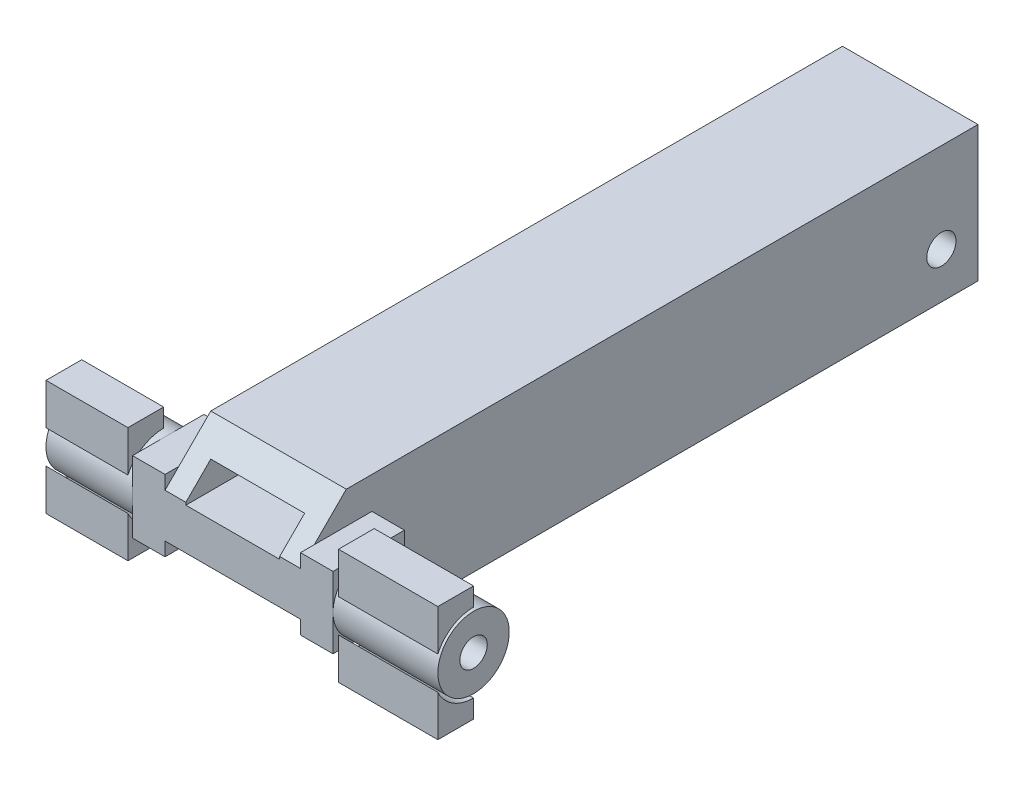
SolidWorks part; units mm, degrees
ref_plane "Спереди" through (0, 0, 0) normal (0, 0, 1) x (1, 0, 0)
ref_plane "Сверху" through (0, 0, 0) normal (0, 1, 0) x (1, 0, 0)
ref_plane "Справа" through (0, 0, 0) normal (1, 0, 0) x (0, 0, -1)
sketch "Эскиз1" plane through (0, 0, 0) normal (1, 0, 0) x (0, 0, -1)
  line L1 (37, -7.4) -> (-37, -7.4)
  line L2 (37, -7.4) -> (37, 7.4)
  line L3 (37, 7.4) -> (-37, 7.4)
  line L4 (-37, -7.4) -> (-37, 7.4)
  line L5 (37, -7.4) -> (-37, 7.4) construction
  line L6 (37, 7.4) -> (-37, -7.4) construction
  point P0 (0, 0)
  dimension "D1" = 14.8
  dimension "D2" = 74
extrude "Бобышка-Вытянуть1" add sketch "Эскиз1" along normal blind 14.8
sketch "Эскиз2" plane through (0, 0, -37) normal (0, 0, -1) x (-1, 0, 0)
  line L0 (0, 7.4) -> (-14.8, -7.4) construction
  line L2 (-2.275, -5.125) -> (-12.525, -5.125)
  line L3 (-2.275, -5.125) -> (-2.275, 5.125)
  line L4 (-2.275, 5.125) -> (-12.525, 5.125)
  line L5 (-12.525, -5.125) -> (-12.525, 5.125)
  line L6 (-2.275, -5.125) -> (-12.525, 5.125) construction
  line L7 (-2.275, 5.125) -> (-12.525, -5.125) construction
  point P4 (-7.4, 0)
  dimension "D1" = 10.25
extrude "Вырез-Вытянуть1" cut sketch "Эскиз2" against normal blind 65
sketch "Эскиз3" plane through (14.8, 0, 0) normal (1, 0, 0) x (0, 0, -1)
  line L0 (37, 0) -> (-37, 0) construction
  line L1 (37, -7.4) -> (37, 7.4) construction
  line L2 (-37, 7.4) -> (-37, -7.4) construction
  circle A0 centre (-33.1, 0) radius 3.9
  dimension "D1" = 7.8
extrude "Бобышка-Вытянуть2" add sketch "Эскиз3" along normal blind 15
sketch "Эскиз4" plane through (0, 0, 0) normal (-1, 0, 0) x (0, 0, 1)
  line L0 (37, 0) -> (-37, 0) construction
  line L1 (37, 7.4) -> (37, -7.4) construction
  line L2 (-37, -7.4) -> (-37, 7.4) construction
  circle A0 centre (33.1, 0) radius 3.9
  dimension "D1" = 7.8
extrude "Бобышка-Вытянуть3" add sketch "Эскиз4" along normal blind 13
chamfer "Фаска1" distance 5 angle 45 2 edges at (7.4, -7.4, 37) (7.4, 7.4, 37)
sketch "Эскиз8" plane through (29.8, 0, 0) normal (1, 0, 0) x (0, 0, -1)
  circle A0 centre (-33.1, 0) radius 1.45
  dimension "D1" = 2.9
extrude "Вырез-Вытянуть4" cut sketch "Эскиз8" against normal through all
sketch "Эскиз9" plane through (0, 0, 0) normal (-1, 0, 0) x (0, 0, 1)
  line L1 (37, -3.9) -> (29.2, -3.9)
  line L2 (37, -3.9) -> (37, 3.9)
  line L3 (37, 3.9) -> (29.2, 3.9)
  line L4 (29.2, -3.9) -> (29.2, 3.9)
  line L5 (37, -3.9) -> (29.2, 3.9) construction
  line L6 (37, 3.9) -> (29.2, -3.9) construction
  circle A0 centre (33.1, 0) radius 3.9 construction
  circle A1 centre (33.1, 0) radius 1.5
  point P0 (33.1, 0)
  point P6 (29.2, 0)
  point P11 (33.1, 3.9)
  dimension "D1" = 3
extrude "Бобышка-Вытянуть4" add sketch "Эскиз9" along normal blind 3.55
sketch "Эскиз10" plane through (14.8, 0, 0) normal (1, 0, 0) x (0, 0, -1)
  line L1 (-37, -3.9) -> (-29.2, -3.9)
  line L2 (-37, -3.9) -> (-37, 3.9)
  line L3 (-37, 3.9) -> (-29.2, 3.9)
  line L4 (-29.2, -3.9) -> (-29.2, 3.9)
  line L5 (-37, -3.9) -> (-29.2, 3.9) construction
  line L6 (-37, 3.9) -> (-29.2, -3.9) construction
  circle A0 centre (-33.1, 0) radius 3.9 construction
  point P0 (-33.1, 0)
  point P6 (-29.2, 0)
  point P9 (-33.1, 3.9)
extrude "Бобышка-Вытянуть5" add sketch "Эскиз10" along normal blind 3.55
sketch "Sketch1" plane through (0, 0, 0) normal (-1, 0, 0) x (0, 0, 1)
  line L0 (-33, 7.4) -> (-33, -7.4) construction
  line L7 (-37, 7.4) -> (32, 7.4) construction
  line L8 (32, -7.4) -> (-37, -7.4) construction
  line L9 (-37, -7.4) -> (-37, 7.4) construction
  circle A0 centre (-33, -2.4) radius 1.6
  dimension "D1" = 3.2
  dimension "D2" = 4
  dimension "D3" = 5
extrude "Cut-Extrude1" cut sketch "Sketch1" against normal through all
sketch "Sketch2" plane through (29.8, 0, 0) normal (1, 0, 0) x (0, 0, -1)
  circle A0 centre (-33.1, 0) radius 1.5
extrude "Cut-Extrude2" cut sketch "Sketch2" against normal through all
sketch "Sketch3" plane through (0, 0, 28) normal (0, 0, -1) x (-1, 0, 0)
  line L0 (-7.4, 5.125) -> (-7.4, -5.125) construction
  line L1 (-2.275, 5.125) -> (-12.525, 5.125) construction
  line L2 (-12.525, -5.125) -> (-2.275, -5.125) construction
  line L4 (-2.275, 2.125) -> (-12.525, 2.125)
  line L5 (-2.275, 2.125) -> (-2.275, 5.125)
  line L6 (-2.275, 5.125) -> (-12.525, 5.125)
  line L7 (-12.525, 2.125) -> (-12.525, 5.125)
  line L8 (-2.275, 2.125) -> (-12.525, 5.125) construction
  line L9 (-2.275, 5.125) -> (-12.525, 2.125) construction
  point P6 (-7.4, 3.625)
  dimension "D1" = 3
extrude "Cut-Extrude3" cut sketch "Sketch3" against normal through all
sketch "Sketch4" plane through (-13, 0, 0) normal (-1, 0, 0) x (0, 0, 1)
  line L0 (33.1, 0) -> (33.1, 6.1479) construction
  line L1 (33.1, 0) -> (33.1, -7.4723) construction
  line L2 (33.1, 4.3) -> (33.1, 6.3)
  line L3 (33.1, 6.3) -> (37, 6.3)
  line L4 (37, 6.3) -> (37, -6.3) construction
  line L5 (37, -6.3) -> (33.1, -6.3)
  line L6 (33.1, -6.3) -> (33.1, -4.3)
  line L7 (37, 0) -> (37, 3.9) construction
  line L8 (37, -1.8111) -> (37, -6.3)
  line L9 (37, 1.8111) -> (37, 6.3)
  circle A0 centre (33.1, 0) radius 3.9 construction
  arc A1 (33.1, 4.3) -> (33.1, -4.3) centre (33.1, 0) cw construction
  arc A2 (33.1, 4.3) -> (37, 1.8111) centre (33.1, 0) cw
  arc A3 (33.1, -4.3) -> (37, -1.8111) centre (33.1, 0) ccw
  point P19 (0, 0)
  dimension "D1" = 0.4
  dimension "D2" = 2
extrude "Boss-Extrude1" add sketch "Sketch4" against normal offset from surface (8.95 mm away) 0.5 separate body up to face at (-3.55, 2.8692, 35.9692)
sketch "Sketch8" plane through (-4.05, 0, 0) normal (1, 0, 0) x (0, 0, -1)
  line L0 (-33.1, -4.3) -> (-33.1, -6.3)
  line L1 (-33.1, -6.3) -> (-37, -6.3)
  line L2 (-37, -6.3) -> (-37, -1.8111)
  line L3 (-33.1, 4.3) -> (-33.1, 6.3)
  line L4 (-33.1, 6.3) -> (-37, 6.3)
  line L5 (-37, 6.3) -> (-37, 1.8111)
  arc A0 (-33.1, 4.3) -> (-37, 1.8111) centre (-33.1, 0) ccw
  arc A1 (-33.1, -4.3) -> (-37, -1.8111) centre (-33.1, 0) cw
extrude "Boss-Extrude7" add sketch "Sketch8" along normal up to surface (10.85 mm away) from offset 23 separate body up to face at (29.8, 0, 31.6)
